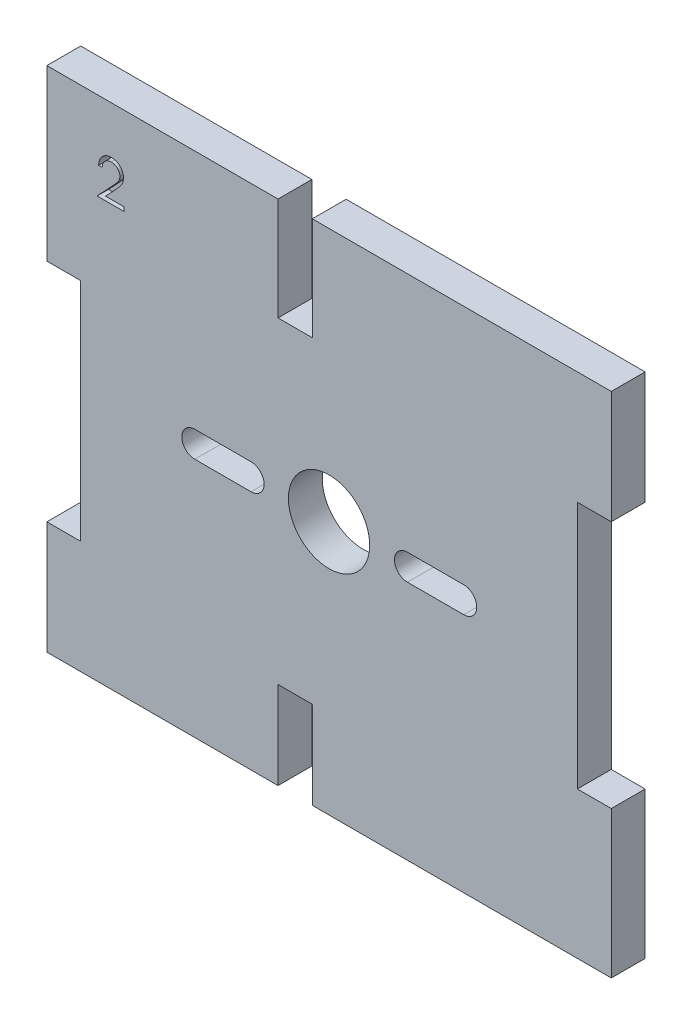
SolidWorks part; units mm, degrees
ref_plane "前视基准面" through (0, 0, 0) normal (0, 0, 1) x (1, 0, 0)
ref_plane "上视基准面" through (0, 0, 0) normal (0, 1, 0) x (1, 0, 0)
ref_plane "右视基准面" through (0, 0, 0) normal (1, 0, 0) x (0, 0, -1)
ref_plane "基准面4" through (0, 0, 3) normal (0, 0, 1) x (1, 0, 0)
sketch "草图1" plane through (0, 0, 3) normal (0, 0, 1) x (1, 0, 0)
  line L0 (9.2367, 23.6493) -> (14.2266, 23.6493)
  line L1 (14.2266, 21.3493) -> (9.2367, 21.3493)
  line L2 (46.1319, 44.9999) -> (19.6452, 44.9999)
  line L3 (19.6452, 44.9999) -> (19.6452, 35.878)
  line L4 (19.6452, 35.878) -> (16.61, 35.878)
  line L5 (16.61, 35.878) -> (16.61, 44.9999)
  line L6 (16.61, 44.9999) -> (-3.8674, 44.9999)
  line L7 (-3.8674, 44.9999) -> (-3.8674, 29.9998)
  line L8 (-3.8674, 29.9998) -> (-0.8673, 29.9998)
  line L9 (-0.8673, 29.9998) -> (-0.8673, 9.9991)
  line L10 (-0.8673, 9.9991) -> (-3.8674, 9.9991)
  line L11 (-3.8674, 9.9991) -> (-3.8674, 0)
  line L12 (-3.8674, 0) -> (16.61, 0)
  line L13 (16.61, 0) -> (16.61, 7.7548)
  line L14 (16.61, 7.7548) -> (19.6452, 7.7548)
  line L15 (19.6452, 7.7548) -> (19.6452, 0)
  line L16 (19.6452, 0) -> (46.1319, 0)
  line L17 (46.1319, 0) -> (46.1319, 13.0005)
  line L18 (46.1319, 13.0005) -> (43.1319, 13.0005)
  line L19 (43.1319, 13.0005) -> (43.1319, 34.9994)
  line L20 (43.1319, 34.9994) -> (46.1319, 34.9994)
  line L21 (46.1319, 34.9994) -> (46.1319, 44.9999)
  line L22 (33.0644, 21.3369) -> (28.0745, 21.3368)
  line L23 (28.0745, 23.6369) -> (33.0644, 23.6369)
  line L24 (18.1276, 35.878) -> (18.1276, 7.7548) construction
  arc A0 (14.2266, 23.6493) -> (14.2266, 21.3493) centre (14.2266, 22.4993) cw
  arc A1 (9.2367, 21.3493) -> (9.2367, 23.6493) centre (9.2367, 22.4993) cw
  arc A2 (33.0644, 23.6369) -> (33.0644, 21.3369) centre (33.0644, 22.4869) cw
  arc A3 (28.0745, 21.3368) -> (28.0745, 23.6369) centre (28.0745, 22.4869) cw
  circle A4 centre (21.1317, 22.4992) radius 3.6
extrude "凸台-拉伸1" add sketch "草图1" against normal blind 3
sketch "草图3" plane through (0, 0, 3) normal (0, 0, 1) x (1, 0, 0)
  text T0 "2"
extrude "切除-拉伸2" cut sketch "草图3" against normal blind 1
